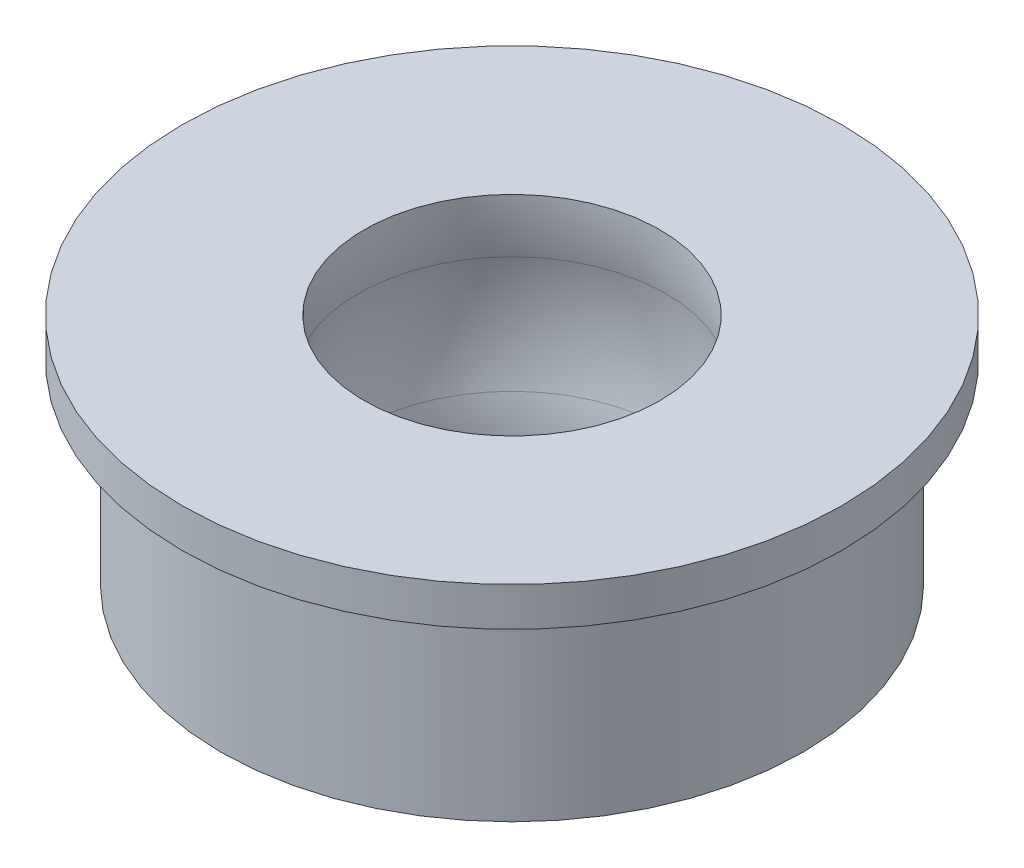
SolidWorks part; units mm, degrees
ref_plane "Front Plane" through (0, 0, 0) normal (0, 0, 1) x (1, 0, 0)
ref_plane "Top Plane" through (0, 0, 0) normal (0, 1, 0) x (1, 0, 0)
ref_plane "Right Plane" through (0, 0, 0) normal (1, 0, 0) x (0, 0, -1)
sketch "Sketch1" plane through (0, 0, 0) normal (0, 1, 0) x (1, 0, 0)
  circle A0 centre (0, 0) radius 3.05
  circle A1 centre (0, 0) radius 6
  dimension "D1" = 6.1
  dimension "D2" = 12
extrude "Boss-Extrude1" add sketch "Sketch1" along normal blind 4
sketch "Sketch2" plane through (0, 4, 0) normal (0, 1, 0) x (1, 0, 0)
  circle A0 centre (0, 0) radius 3.05 construction
  circle A1 centre (0, 0) radius 3.05
  circle A2 centre (0, 0) radius 6.8
  dimension "D1" = 13.6
extrude "Boss-Extrude2" add sketch "Sketch2" along normal blind 0.8
sketch "Sketch3" plane through (0, 0, 0) normal (0, 0, 1) x (1, 0, 0)
  line L0 (3.05, 4.8) -> (-3.05, 4.8) construction
  line L1 (3.05, 4.8) -> (-3.05, 4.8)
  line L2 (-6, 0) -> (6, 0) construction
  line L3 (-6, 0) -> (6, 0)
  line L4 (-3.05, 4.8) -> (-3.05, 0)
  line L5 (0, 0) -> (0, 4.8)
  arc A0 (-3.2741, 6.4258) -> (-3.171, 3.6) centre (-9.06, 4.8) cw
  arc A1 (-3.171, 1.2) -> (-3.1477, -1.0792) centre (-9.06, 0) cw
  arc A2 (-3.171, 3.6) -> (-3.171, 1.2) centre (2.718, 2.4) ccw
  point P9 (-3.05, 4.8)
  point P11 (-3.05, 0)
  point P16 (-3.55, 2.4)
  dimension "D1" = 0.5
revolve "Cut-Revolve1" cut sketch "Sketch3" angle 360 about L5
